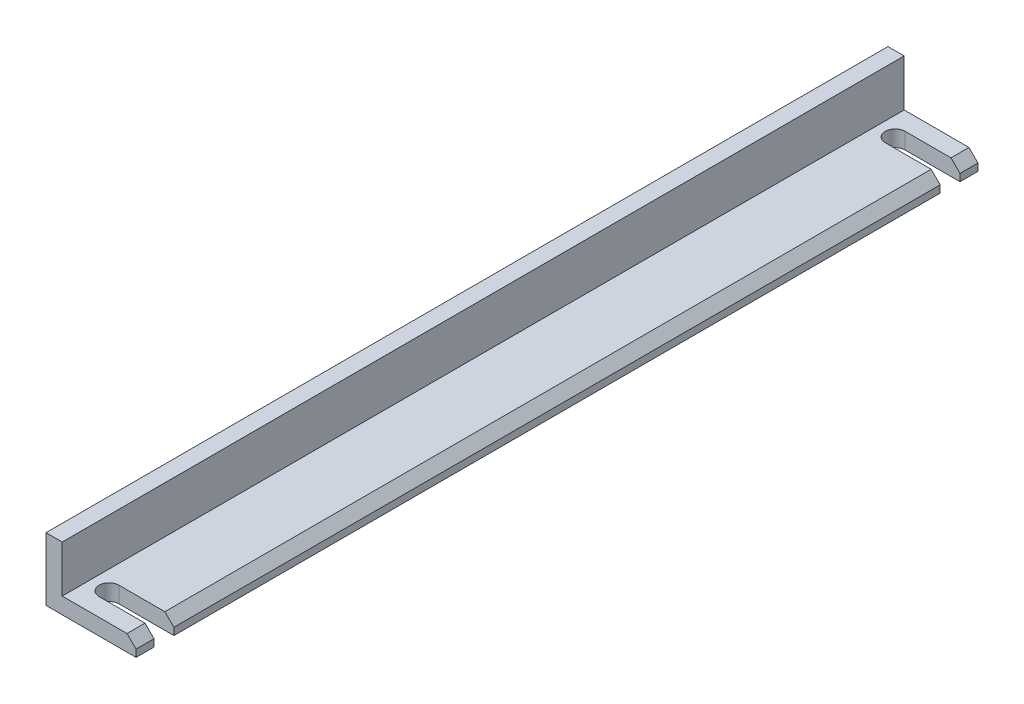
SolidWorks part; units mm, degrees
material "AISI 316 Annealed Stainless Steel Bar (SS)"
ref_plane "Спереди" through (0, 0, 0) normal (0, 0, 1) x (1, 0, 0)
ref_plane "Сверху" through (0, 0, 0) normal (0, 1, 0) x (1, 0, 0)
ref_plane "Справа" through (0, 0, 0) normal (1, 0, 0) x (0, 0, -1)
sketch "Sketch1" plane through (0, 0, 0) normal (0, 0, 1) x (1, 0, 0)
  line L0 (0, 0) -> (0, 7)
  line L1 (0, 0) -> (10, 0)
  dimension "D1" = 10
  dimension "D2" = 7
extrude "Extrude-Thin1" add sketch "Sketch1" along normal mid plane 93.5 thin
chamfer "Chamfer1" distance 1 angle 45 1 edges at (10, 1.8, 0)
sketch "Sketch2" plane through (0, 1.8, 0) normal (0, 1, 0) x (1, 0, 0)
  line L0 (11.5225, -43.65) -> (3.9, -43.65) construction
  line L1 (11.5225, -44.75) -> (3.9, -44.75)
  line L2 (11.5225, -42.55) -> (3.9, -42.55)
  line L3 (1.8, -46.75) -> (9, -46.75) construction
  line L4 (1.8, -46.75) -> (1.8, 46.75) construction
  arc A0 (11.5225, -44.75) -> (11.5225, -42.55) centre (11.5225, -43.65) ccw
  arc A1 (3.9, -42.55) -> (3.9, -44.75) centre (3.9, -43.65) ccw
  point P2 (7.7113, -43.65)
  dimension "D3" = 1
  dimension "D1" = 2.2
  dimension "D2" = 2
extrude "Cut-Extrude1" cut sketch "Sketch2" against normal blind 10
mirror "Mirror1" about plane through (0, 0, 0) normal (0, 0, 1) of "Cut-Extrude1"
